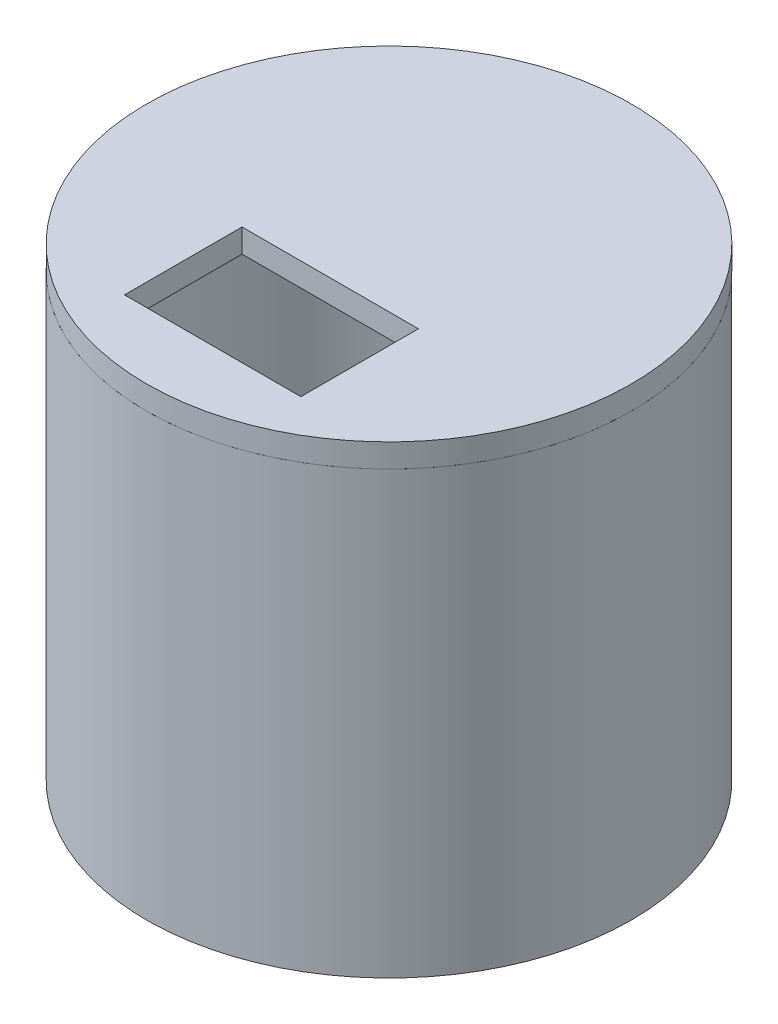
SolidWorks part; units mm, degrees
ref_plane "Front Plane" through (0, 0, 0) normal (0, 0, 1) x (1, 0, 0)
ref_plane "Top Plane" through (0, 0, 0) normal (0, 1, 0) x (1, 0, 0)
ref_plane "Right Plane" through (0, 0, 0) normal (1, 0, 0) x (0, 0, -1)
sketch "Sketch1" plane through (0, 0, 0) normal (0, 1, 0) x (1, 0, 0)
  circle A0 centre (0, 0) radius 80
extrude "Extrude-Thin1" add sketch "Sketch1" along normal blind 150 thin
sketch "Sketch2" plane through (0, 150, 0) normal (0, 1, 0) x (1, 0, 0)
  circle A0 centre (0, 0) radius 82.5
extrude "Boss-Extrude1" add sketch "Sketch2" along normal blind 8 separate body
sketch "Sketch3" plane through (0, 158, 0) normal (0, 1, 0) x (1, 0, 0)
  line L1 (30, -60) -> (-30, -60)
  line L2 (30, -60) -> (30, -20)
  line L3 (30, -20) -> (-30, -20)
  line L4 (-30, -60) -> (-30, -20)
  line L5 (30, -60) -> (-30, -20) construction
  line L6 (30, -20) -> (-30, -60) construction
  point P0 (0, -40)
  point P5 (0, 0)
  point P6 (0, 0)
  dimension "D1" = 30
  dimension "D2" = 20
  dimension "D3" = 30
  dimension "D4" = 40
extrude "Cut-Extrude1" cut sketch "Sketch3" against normal through all contours L3 L4 L1 L2
